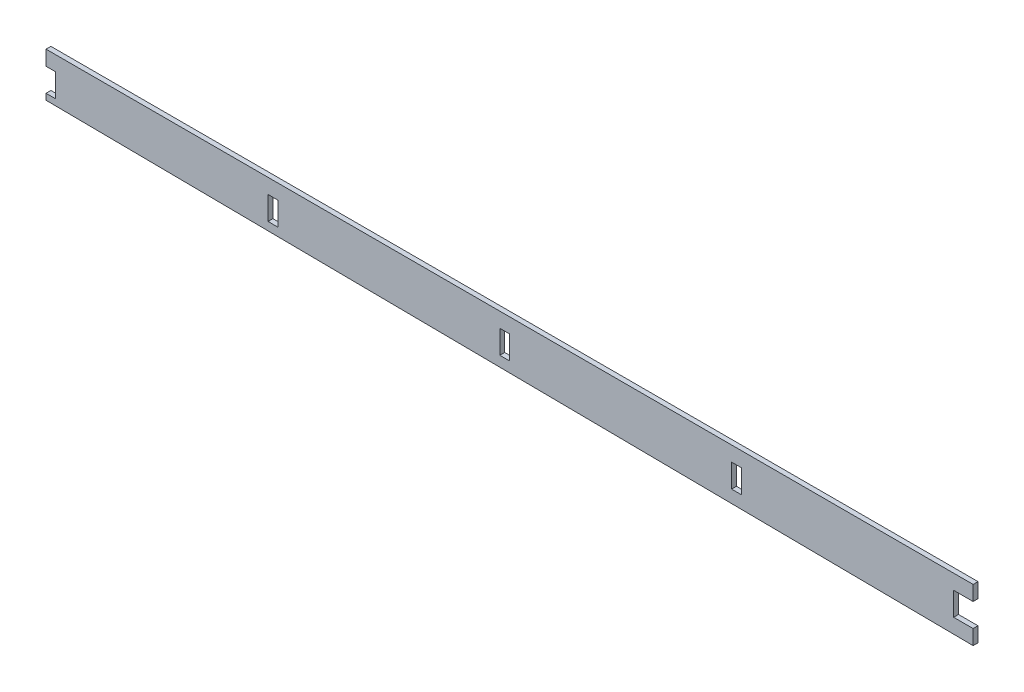
SolidWorks part; units mm, degrees
material "Balsa"
ref_plane "Front Plane" through (0, 0, 0) normal (0, 0, 1) x (1, 0, 0)
ref_plane "Top Plane" through (0, 0, 0) normal (0, 1, 0) x (1, 0, 0)
ref_plane "Right Plane" through (0, 0, 0) normal (1, 0, 0) x (0, 0, -1)
sketch "Sketch1" plane through (0, 0, 0) normal (0, 0, 1) x (1, 0, 0)
  line L0 (88.3257, -43.5125) -> (88.3257, -48.3514)
  line L1 (88.3257, -48.3514) -> (-213.9343, -45.4809)
  line L2 (-213.9343, -45.4809) -> (-213.9343, -43.5125) construction
  line L3 (-210.7593, -45.511) -> (-213.9343, -45.4809) construction
  line L4 (-213.9343, -45.4809) -> (-213.9343, -43.5125)
  line L5 (-213.9343, -43.5125) -> (-210.7593, -43.5125)
  line L6 (-210.7593, -43.5125) -> (-210.7593, -35.8925)
  line L7 (-210.7593, -35.8925) -> (-213.9343, -35.8925)
  line L8 (-213.9343, -35.8925) -> (-213.9343, -31.0536)
  line L9 (81.9757, -43.5125) -> (88.3257, -43.5125)
  line L10 (81.9757, -43.5125) -> (81.9757, -35.8925)
  line L11 (81.9757, -35.8925) -> (88.3257, -35.8925)
  line L12 (88.3257, -35.8925) -> (88.3257, -31.0536)
  line L13 (88.3257, -31.0536) -> (-213.9343, -31.0536)
  line L14 (12.7607, -43.5125) -> (12.7607, -35.8925)
  line L15 (12.7607, -35.8925) -> (9.5857, -35.8925)
  line L16 (9.5857, -35.8925) -> (9.5857, -43.5125)
  line L17 (9.5857, -43.5125) -> (12.7607, -43.5125)
  line L18 (-65.9793, -43.5125) -> (-62.8043, -43.5125)
  line L19 (-62.8043, -43.5125) -> (-62.8043, -35.8925)
  line L20 (-62.8043, -35.8925) -> (-65.9793, -35.8925)
  line L21 (-65.9793, -35.8925) -> (-65.9793, -43.5125)
  line L22 (-141.5443, -43.5125) -> (-138.3693, -43.5125)
  line L23 (-138.3693, -43.5125) -> (-138.3693, -35.8925)
  line L24 (-138.3693, -35.8925) -> (-141.5443, -35.8925)
  line L25 (-141.5443, -35.8925) -> (-141.5443, -43.5125)
extrude "Boss-Extrude1" add sketch "Sketch1" along normal blind 1.5875
